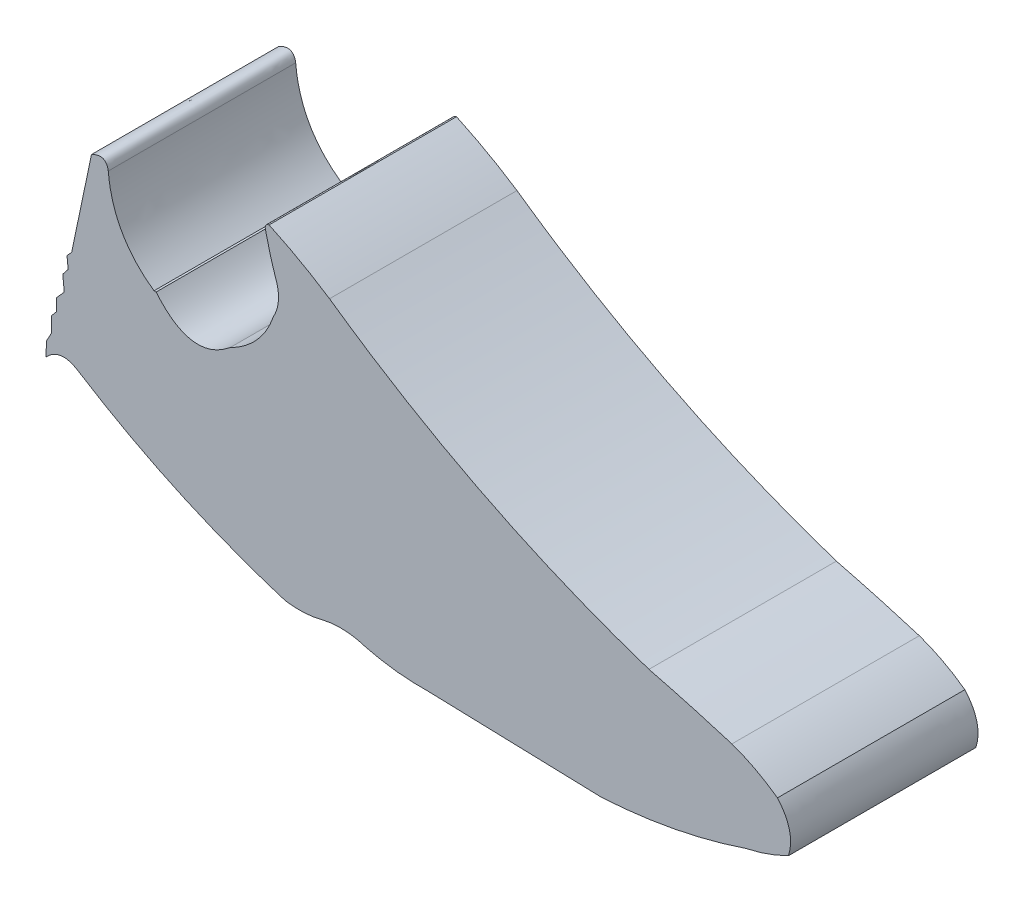
SolidWorks part; units mm, degrees
ref_plane "Front Plane" through (0, 0, 0) normal (0, 0, 1) x (1, 0, 0)
ref_plane "Top Plane" through (0, 0, 0) normal (0, 1, 0) x (1, 0, 0)
ref_plane "Right Plane" through (0, 0, 0) normal (1, 0, 0) x (0, 0, -1)
sketch "Sketch1" plane through (0, 0, 0) normal (0, 0, 1) x (1, 0, 0)
  line L0 (-170.706, 177.6957) -> (495.9607, 177.6957) construction
  line L1 (-151.3085, 320.4483) -> (-153.9029, 320.4483)
  spline S0 degree 1 poles (-230.1464, 426.2663) (-254.3647, 310.7635) knots 0 0 1 1
  spline S1 degree 1 poles (-254.3647, 310.7635) (-260.0242, 304.5665) knots 0 0 1 1
  spline S2 degree 1 poles (-260.0242, 304.5665) (-258.5789, 290.6919) knots 0 0 1 1
  spline S3 degree 1 poles (-258.5789, 290.6919) (-265.1931, 282.3847) knots 0 0 1 1
  spline S4 degree 1 poles (-265.1931, 282.3847) (-263.37, 264.2408) knots 0 0 1 1
  spline S5 degree 1 poles (-263.37, 264.2408) (-272.8462, 253.6803) knots 0 0 1 1
  spline S6 degree 1 poles (-272.8462, 253.6803) (-273.0303, 238.665) knots 0 0 1 1
  spline S7 degree 1 poles (-273.0303, 238.665) (-279.0676, 231.4208) knots 0 0 1 1
  spline S8 degree 1 poles (-279.0676, 231.4208) (-278.8923, 213.4389) knots 0 0 1 1
  spline S9 degree 1 poles (-278.8923, 213.4389) (-285.0371, 201.8869) knots 0 0 1 1
  spline S10 degree 1 poles (-285.0371, 201.8869) (-285.6311, 184.6856) knots 0 0 1 1
  spline S11 degree 2 poles (-285.6311, 184.6856) (-268.0629, 203.2228) (-246.6143, 189.6597) knots 0 0 0 1 1 1
  spline S12 degree 2 poles (-246.6143, 189.6597) (-127.9207, 114.4296) (6.6738, 73.0834) knots 0 0 0 1 1 1
  spline S13 degree 2 poles (6.6738, 73.0834) (28.6667, 69.7581) (50.4437, 75.3113) knots 0 0 0 1 1 1
  spline S14 degree 2 poles (50.4437, 75.3113) (77.6414, 82.0464) (104.7636, 73.0834) knots 0 0 0 1 1 1
  spline S15 degree 2 poles (104.7636, 73.0834) (141.4602, 63.7482) (179.6364, 64.6226) knots 0 0 0 1 1 1
  spline S16 degree 1 poles (179.6364, 64.6226) (392.0822, 58.2922) knots 0 0 1 1
  spline S17 degree 2 poles (392.0822, 58.2922) (482.5671, 63.486) (568.1275, 92.3809) knots 0 0 0 1 1 1
  spline S18 degree 2 poles (568.1275, 92.3809) (595.4307, 98.2339) (619.9632, 110.6637) knots 0 0 0 1 1 1
  spline S19 degree 2 poles (619.9632, 110.6637) (629.0078, 139.2987) (606.4866, 165.0087) knots 0 0 0 1 1 1
  spline S20 degree 2 poles (606.4866, 165.0087) (580.7948, 183.6853) (550.9271, 194.2344) knots 0 0 0 1 1 1
  spline S21 degree 2 poles (550.9271, 194.2344) (500.7258, 209.7112) (449.7603, 222.4227) knots 0 0 0 1 1 1
  spline S22 degree 2 poles (449.7603, 222.4227) (241.2623, 291.7085) (60.1926, 419.0806) knots 0 0 0 1 1 1
  spline S23 degree 2 poles (60.1926, 419.0806) (24.8327, 442.4757) (-13.5619, 460.1903) knots 0 0 0 1 1 1
  spline S24 degree 2 poles (-13.5619, 460.1903) (-19.6649, 459.0464) (-17.822, 452.3808) knots 0 0 0 1 1 1
  spline S25 degree 2 poles (-17.822, 452.3808) (-12.3186, 427.7449) (-4.1382, 403.8612) knots 0 0 0 1 1 1
  spline S26 degree 2 poles (-4.1382, 403.8612) (1.6741, 384.6999) (-8.1643, 366.0809) knots 0 0 0 1 1 1
  spline S27 degree 2 poles (-8.1643, 366.0809) (-21.9736, 326.4011) (-61.0452, 306.8629) knots 0 0 0 1 1 1
  spline S28 degree 2 poles (-61.0452, 306.8629) (-108.2304, 268.5951) (-151.3085, 320.4483) knots 0 0 0 1 1 1
  spline S29 degree 2 poles (-153.9029, 320.4483) (-204.1936, 355.8303) (-209.682, 419.0806) knots 0 0 0 1 1 1
  spline S30 degree 2 poles (-209.682, 419.0806) (-212.469, 435.6351) (-230.1464, 426.2663) knots 0 0 0 1 1 1
extrude "Boss-Extrude1" add sketch "Sketch1" along normal blind 228.6
